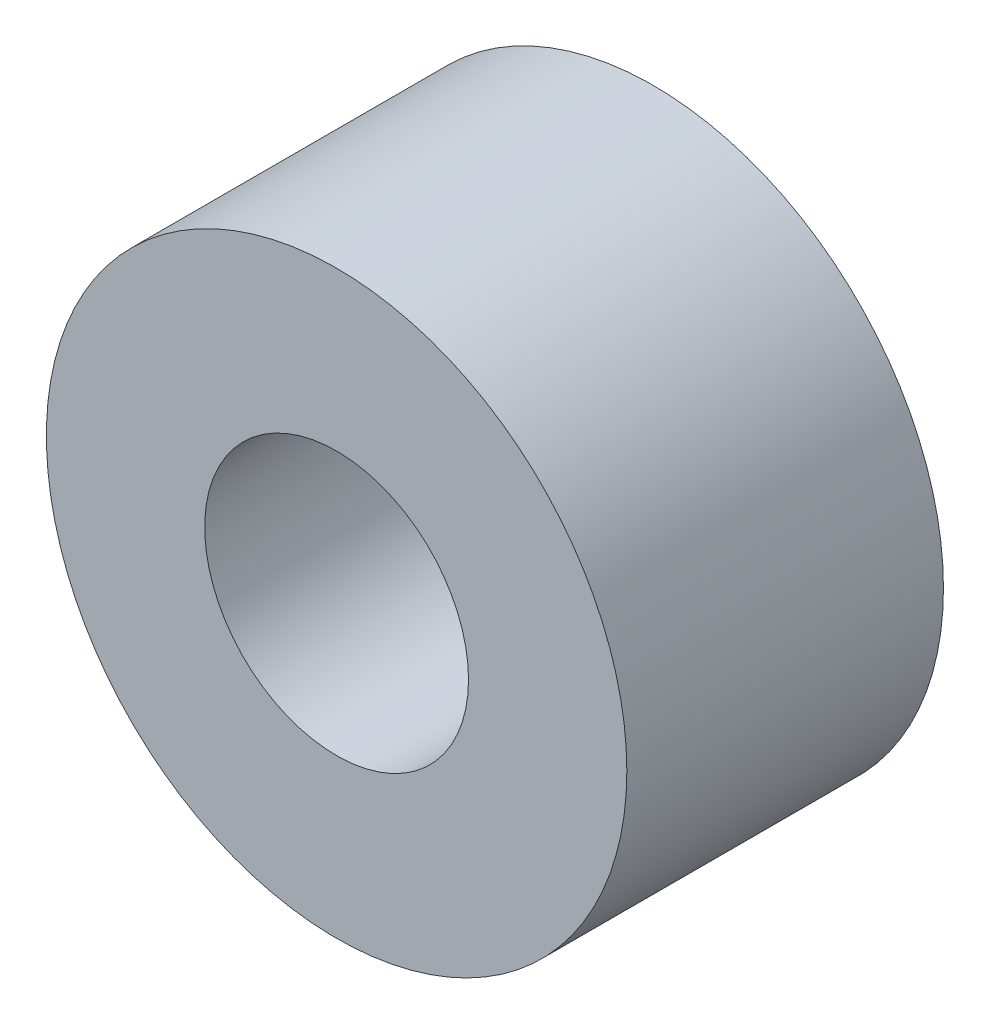
SolidWorks part; units mm, degrees
ref_plane "정면" through (0, 0, 0) normal (0, 0, 1) x (1, 0, 0)
ref_plane "윗면" through (0, 0, 0) normal (0, 1, 0) x (1, 0, 0)
ref_plane "우측면" through (0, 0, 0) normal (1, 0, 0) x (0, 0, -1)
sketch "스케치1" plane through (0, 0, 0) normal (0, 0, 1) x (1, 0, 0)
  circle A0 centre (0, 0) radius 5.5
  circle A1 centre (0, 0) radius 2.5
  dimension "D1" = 11
  dimension "D2" = 5
extrude "보스-돌출1" add sketch "스케치1" along normal blind 6
